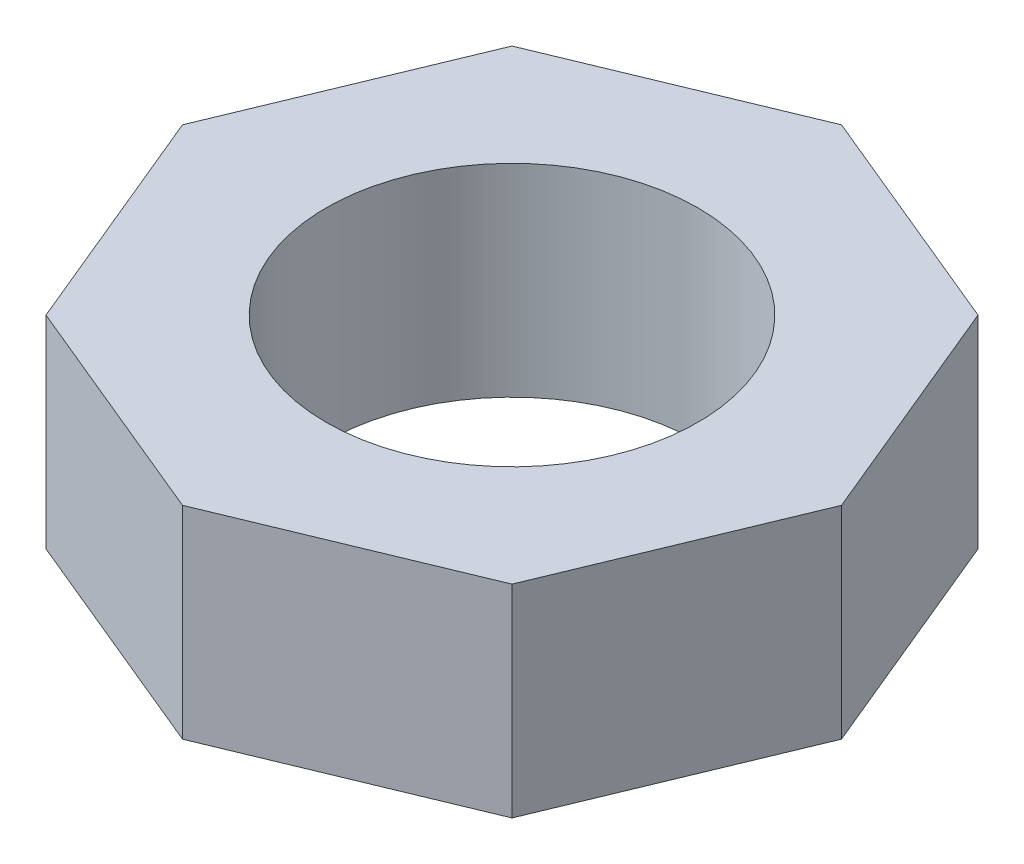
SolidWorks part; units mm, degrees
ref_plane "Front" through (0, 0, 0) normal (0, 0, 1) x (1, 0, 0)
ref_plane "Top" through (0, 0, 0) normal (0, 1, 0) x (1, 0, 0)
ref_plane "Right" through (0, 0, 0) normal (1, 0, 0) x (0, 0, -1)
sketch "Sketch1" plane through (0, 0, 0) normal (0, 1, 0) x (1, 0, 0)
  line L1 (2.522, 0) -> (1.7833, 1.7833)
  line L2 (1.7833, 1.7833) -> (0, 2.522)
  line L3 (0, 2.522) -> (-1.7833, 1.7833)
  line L4 (-1.7833, 1.7833) -> (-2.522, 0)
  line L5 (-2.522, 0) -> (-1.7833, -1.7833)
  line L6 (-1.7833, -1.7833) -> (0, -2.522)
  line L7 (0, -2.522) -> (1.7833, -1.7833)
  line L8 (1.7833, -1.7833) -> (2.522, 0)
  circle A0 centre (0, 0) radius 2.33 construction
  circle A1 centre (0, 0) radius 1.4225
  dimension "D1" = 4.66
  dimension "D2" = 2.845
extrude "Boss-Extrude1" add sketch "Sketch1" along normal blind 1.55
